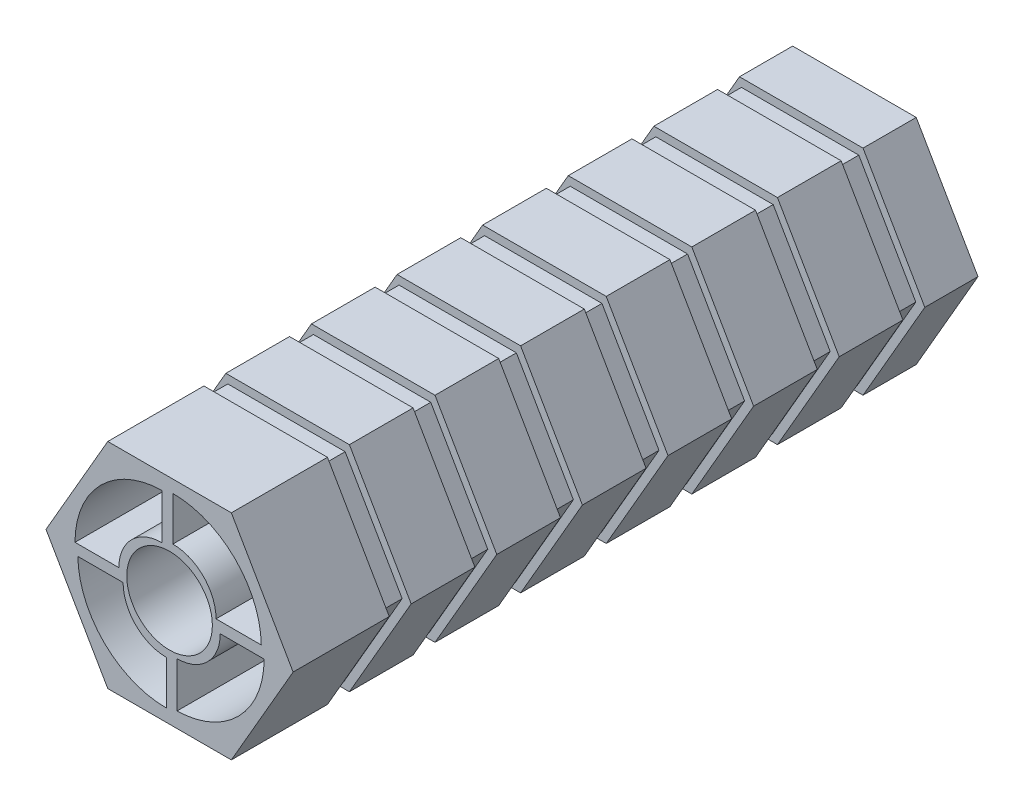
SolidWorks part; units mm, degrees
ref_plane "Front Plane" through (0, 0, 0) normal (0, 0, 1) x (1, 0, 0)
ref_plane "Top Plane" through (0, 0, 0) normal (0, 1, 0) x (1, 0, 0)
ref_plane "Right Plane" through (0, 0, 0) normal (1, 0, 0) x (0, 0, -1)
sketch "Sketch1" plane through (0, 0, 0) normal (0, 0, 1) x (1, 0, 0)
  line L1 (-14.4338, 0) -> (-7.2169, -12.5)
  line L2 (-7.2169, -12.5) -> (7.2169, -12.5)
  line L3 (7.2169, -12.5) -> (14.4338, 0)
  line L4 (14.4338, 0) -> (7.2169, 12.5)
  line L5 (7.2169, 12.5) -> (-7.2169, 12.5)
  line L6 (-7.2169, 12.5) -> (-14.4338, 0)
  circle A0 centre (0, 0) radius 5
  circle A1 centre (0, 0) radius 12.5 construction
  dimension "D1" = 10
  dimension "D2" = 25
extrude "Boss-Extrude1" add sketch "Sketch1" along normal blind 40
sketch "Sketch2" plane through (0, 0, 40) normal (0, 0, 1) x (1, 0, 0)
  line L0 (-0.8762, 10.7144) -> (-0.8762, 5.4289)
  line L1 (-5.9214, 0.3836) -> (-11.0468, 0.3836)
  line L2 (7.2169, 12.5) -> (-7.2169, 12.5) construction
  line L3 (10.7144, 0.8762) -> (5.4289, 0.8762)
  line L4 (0.3836, 5.9214) -> (0.3836, 11.0468)
  line L5 (0.8762, -10.7144) -> (0.8762, -5.4289)
  line L6 (5.9214, -0.3836) -> (11.0468, -0.3836)
  line L7 (-10.7144, -0.8762) -> (-5.4289, -0.8762)
  line L8 (-0.3836, -5.9214) -> (-0.3836, -11.0468)
  arc A0 (-0.8762, 5.4289) -> (-5.9214, 0.3836) centre (-0.8762, 0.3836) ccw
  arc A1 (-11.0468, 0.3836) -> (-0.8762, 10.7144) centre (-0.7147, 0.3836) cw
  arc A2 (0.3836, 11.0468) -> (10.7144, 0.8762) centre (0.3836, 0.7147) cw
  arc A3 (5.4289, 0.8762) -> (0.3836, 5.9214) centre (0.3836, 0.8762) ccw
  arc A4 (11.0468, -0.3836) -> (0.8762, -10.7144) centre (0.7147, -0.3836) cw
  arc A5 (0.8762, -5.4289) -> (5.9214, -0.3836) centre (0.8762, -0.3836) ccw
  arc A6 (-0.3836, -11.0468) -> (-10.7144, -0.8762) centre (-0.3836, -0.7147) cw
  arc A7 (-5.4289, -0.8762) -> (-0.3836, -5.9214) centre (-0.3836, -0.8762) ccw
  point P30 (0, 0)
  dimension "D1" = 10.3321
  dimension "D4" = 1.7856
  dimension "D2" = 5.2855
  dimension "D3" = 5.1254
  dimension "D5" = 3.387
  dimension "D6" = 4
extrude "Cut-Extrude1" cut sketch "Sketch2" against normal through all
sketch "Sketch6" plane through (0, 0, 0) normal (0, 0, -1) x (-1, 0, 0)
  line L0 (-5.4289, 0.8762) -> (-10.7144, 0.8762) construction
  line L1 (-0.3836, 11.0468) -> (-0.3836, 5.9214) construction
  line L2 (-0.8762, -5.4289) -> (-0.8762, -10.7144) construction
  line L3 (0.3836, -11.0468) -> (0.3836, -5.9214) construction
  line L4 (5.4289, -0.8762) -> (10.7144, -0.8762) construction
  line L5 (11.0468, 0.3836) -> (5.9214, 0.3836) construction
  line L6 (14.4338, 0) -> (7.2169, 12.5)
  line L7 (7.2169, 12.5) -> (-7.2169, 12.5)
  line L8 (-7.2169, 12.5) -> (-14.4338, 0)
  line L9 (-14.4338, 0) -> (-7.2169, -12.5)
  line L10 (-7.2169, -12.5) -> (7.2169, -12.5)
  line L11 (7.2169, -12.5) -> (14.4338, 0)
  line L12 (14.4338, 0) -> (7.2169, 12.5)
  line L13 (7.2169, 12.5) -> (-7.2169, 12.5)
  line L14 (-7.2169, 12.5) -> (-14.4338, 0)
  line L15 (-14.4338, 0) -> (-7.2169, -12.5)
  line L16 (-7.2169, -12.5) -> (7.2169, -12.5)
  line L17 (7.2169, -12.5) -> (14.4338, 0)
  line L18 (0.8762, 5.4289) -> (0.8762, 10.7144) construction
  line L19 (-0.8762, -5.4289) -> (-0.8762, -10.7144)
  line L20 (0.3836, -11.0468) -> (0.3836, -5.9214)
  line L21 (5.4289, -0.8762) -> (10.7144, -0.8762)
  line L22 (11.0468, 0.3836) -> (5.9214, 0.3836)
  line L23 (0.8762, 5.4289) -> (0.8762, 10.7144)
  line L24 (-0.3836, 11.0468) -> (-0.3836, 5.9214)
  line L25 (-5.4289, 0.8762) -> (-10.7144, 0.8762)
  arc A0 (-0.3836, 5.9214) -> (-5.4289, 0.8762) centre (-0.3836, 0.8762) ccw construction
  arc A1 (-0.3836, 5.9214) -> (-5.4289, 0.8762) centre (-0.3836, 0.8762) ccw
  arc A2 (-0.3836, 11.0468) -> (-10.7144, 0.8762) centre (-0.3836, 0.7147) ccw construction
  circle A3 centre (0, 0) radius 5 construction
  arc A4 (0.3836, -11.0468) -> (10.7144, -0.8762) centre (0.3836, -0.7147) ccw construction
  arc A5 (-11.0468, -0.3836) -> (-0.8762, -10.7144) centre (-0.7147, -0.3836) ccw construction
  arc A6 (0.3836, -5.9214) -> (5.4289, -0.8762) centre (0.3836, -0.8762) ccw construction
  arc A7 (5.9214, 0.3836) -> (0.8762, 5.4289) centre (0.8762, 0.3836) ccw construction
  arc A8 (11.0468, 0.3836) -> (0.8762, 10.7144) centre (0.7147, 0.3836) ccw construction
  circle A9 centre (0, 0) radius 5
  arc A10 (0.3836, -11.0468) -> (10.7144, -0.8762) centre (0.3836, -0.7147) ccw
  arc A11 (-11.0468, -0.3836) -> (-0.8762, -10.7144) centre (-0.7147, -0.3836) ccw
  arc A12 (0.3836, -5.9214) -> (5.4289, -0.8762) centre (0.3836, -0.8762) ccw
  arc A13 (5.9214, 0.3836) -> (0.8762, 5.4289) centre (0.8762, 0.3836) ccw
  arc A14 (11.0468, 0.3836) -> (0.8762, 10.7144) centre (0.7147, 0.3836) ccw
  arc A15 (-0.3836, 11.0468) -> (-10.7144, 0.8762) centre (-0.3836, 0.7147) ccw
  line M8 (5.4289, -0.8762) -> (10.7144, -0.8762)
  arc M9 (10.7144, -0.8762) -> (0.3836, -11.0468) centre (0.3836, -0.7147) cw
  line M10 (0.3836, -11.0468) -> (0.3836, -5.9214)
  arc M11 (0.3836, -5.9214) -> (5.4289, -0.8762) centre (0.3836, -0.8762) ccw
  line M12 (-0.8762, -5.4289) -> (-0.8762, -10.7144)
  arc M13 (-0.8762, -10.7144) -> (-11.0468, -0.3836) centre (-0.7147, -0.3836) cw
  line M14 (-11.0468, -0.3836) -> (-5.9214, -0.3836)
  arc M15 (-5.9214, -0.3836) -> (-0.8762, -5.4289) centre (-0.8762, -0.3836) ccw
  line M16 (-5.4289, 0.8762) -> (-10.7144, 0.8762)
  arc M17 (-10.7144, 0.8762) -> (-0.3836, 11.0468) centre (-0.3836, 0.7147) cw
  line M18 (-0.3836, 11.0468) -> (-0.3836, 5.9214)
  arc M19 (-0.3836, 5.9214) -> (-5.4289, 0.8762) centre (-0.3836, 0.8762) ccw
  line M20 (0.8762, 5.4289) -> (0.8762, 10.7144)
  arc M21 (0.8762, 10.7144) -> (11.0468, 0.3836) centre (0.7147, 0.3836) cw
  line M22 (11.0468, 0.3836) -> (5.9214, 0.3836)
  arc M23 (5.9214, 0.3836) -> (0.8762, 5.4289) centre (0.8762, 0.3836) ccw
  line M24 (14.4338, 0) -> (7.2169, 12.5)
  line M25 (7.2169, 12.5) -> (-7.2169, 12.5)
  line M26 (-7.2169, 12.5) -> (-14.4338, 0)
  line M27 (-14.4338, 0) -> (-7.2169, -12.5)
  line M28 (-7.2169, -12.5) -> (7.2169, -12.5)
  line M29 (7.2169, -12.5) -> (14.4338, 0)
  circle M30 centre (0, 0) radius 5
  dimension "D1" = 0
extrude "Boss-Extrude2" add sketch "Sketch6" along normal blind 40 contours M29 M24 M25 M26 M27 M28 M30 M23 M20 M21 M22 M19 M16 M17 M18 M15 M12 M13 M14 M11 M8 M9 M10
sketch "Sketch7" plane through (0, -12.5, 0) normal (0, -1, 0) x (1, 0, 0)
  line L0 (-8.4898, -31.2288) -> (-5.5034, -31.2288)
  line L1 (-5.5034, -31.2288) -> (-5.5034, -33.7886)
  line L2 (-5.5034, -33.7886) -> (-8.4898, -33.7886)
  line L3 (-8.4898, -33.7886) -> (-8.4898, -31.2288)
  line L4 (0, 0) -> (0, -49.4423) construction
extrude "Cut-Extrude2" cut sketch "Sketch7" along direction (-0.5, 0.866, 0) on the side against the normal blind 24
sketch "Sketch9" plane through (-10.8253, -6.25, 0) normal (-0.866, -0.5, 0) x (0, 0, 1)
  line L0 (-33.7886, 6.4328) -> (-31.2288, 6.4328)
  line L1 (-33.7886, -7.2169) -> (-33.7886, 7.2169) construction
  line L2 (-31.2288, 8.0736) -> (-31.2288, -0.0895) construction
  line L3 (-31.2288, 6.4328) -> (-31.2288, 8.0736)
  line L4 (-31.2288, 8.0736) -> (-33.7886, 8.0736)
  line L5 (-33.7886, 8.0736) -> (-33.7886, 6.4328)
  line L6 (-23.7886, 8.0736) -> (-23.7886, 6.4328)
  line L7 (-21.2288, 8.0736) -> (-23.7886, 8.0736)
  line L8 (-13.7886, 8.0736) -> (-13.7886, 6.4328)
  line L9 (-11.2288, 8.0736) -> (-13.7886, 8.0736)
  line L10 (-3.7886, 8.0736) -> (-3.7886, 6.4328)
  line L11 (-1.2288, 8.0736) -> (-3.7886, 8.0736)
  line L12 (6.2114, 8.0736) -> (6.2114, 6.4328)
  line L13 (8.7712, 8.0736) -> (6.2114, 8.0736)
  line L14 (16.2114, 8.0736) -> (16.2114, 6.4328)
  line L15 (18.7712, 8.0736) -> (16.2114, 8.0736)
  line L16 (26.2114, 8.0736) -> (26.2114, 6.4328)
  line L17 (28.7712, 8.0736) -> (26.2114, 8.0736)
  line L18 (-23.7886, 6.4328) -> (-21.2288, 6.4328)
  line L19 (-21.2288, 6.4328) -> (-21.2288, 8.0736)
  line L20 (-13.7886, 6.4328) -> (-11.2288, 6.4328)
  line L21 (-11.2288, 6.4328) -> (-11.2288, 8.0736)
  line L22 (-3.7886, 6.4328) -> (-1.2288, 6.4328)
  line L23 (-1.2288, 6.4328) -> (-1.2288, 8.0736)
  line L24 (6.2114, 6.4328) -> (8.7712, 6.4328)
  line L25 (8.7712, 6.4328) -> (8.7712, 8.0736)
  line L26 (16.2114, 6.4328) -> (18.7712, 6.4328)
  line L27 (18.7712, 6.4328) -> (18.7712, 8.0736)
  line L28 (26.2114, 6.4328) -> (28.7712, 6.4328)
  line L29 (28.7712, 6.4328) -> (28.7712, 8.0736)
  dimension "D1" = 7
extrude "Cut-Extrude3" cut sketch "Sketch9" along direction (0.5, 0.866, 0) on the side against the normal blind 24
sketch "Sketch10" plane through (0, -12.5, 0) normal (0, -1, 0) x (1, 0, 0)
  line L1 (-5.5034, -33.7886) -> (-5.5034, -31.2288)
  line L2 (-5.5034, -31.2288) -> (-8.6605, -31.2288)
  line L3 (-14.4338, -31.2288) -> (-7.2169, -31.2288) construction
  line L4 (-8.6605, -31.2288) -> (-8.6605, -33.7886)
  line L5 (-7.2169, -33.7886) -> (-14.4338, -33.7886) construction
  line L6 (-8.6605, -33.7886) -> (-5.5034, -33.7886)
  line L7 (-8.6605, -21.2288) -> (-8.6605, -23.7886)
  line L8 (-8.6605, -23.7886) -> (-5.5034, -23.7886)
  line L9 (-8.6605, -11.2288) -> (-8.6605, -13.7886)
  line L10 (-8.6605, -13.7886) -> (-5.5034, -13.7886)
  line L11 (-8.6605, -1.2288) -> (-8.6605, -3.7886)
  line L12 (-8.6605, -3.7886) -> (-5.5034, -3.7886)
  line L13 (-8.6605, 8.7712) -> (-8.6605, 6.2114)
  line L14 (-8.6605, 6.2114) -> (-5.5034, 6.2114)
  line L15 (-8.6605, 18.7712) -> (-8.6605, 16.2114)
  line L16 (-8.6605, 16.2114) -> (-5.5034, 16.2114)
  line L17 (-8.6605, 28.7712) -> (-8.6605, 26.2114)
  line L18 (-8.6605, 26.2114) -> (-5.5034, 26.2114)
  line L19 (-5.5034, -23.7886) -> (-5.5034, -21.2288)
  line L20 (-5.5034, -21.2288) -> (-8.6605, -21.2288)
  line L21 (-5.5034, -13.7886) -> (-5.5034, -11.2288)
  line L22 (-5.5034, -11.2288) -> (-8.6605, -11.2288)
  line L23 (-5.5034, -3.7886) -> (-5.5034, -1.2288)
  line L24 (-5.5034, -1.2288) -> (-8.6605, -1.2288)
  line L25 (-5.5034, 6.2114) -> (-5.5034, 8.7712)
  line L26 (-5.5034, 8.7712) -> (-8.6605, 8.7712)
  line L27 (-5.5034, 16.2114) -> (-5.5034, 18.7712)
  line L28 (-5.5034, 18.7712) -> (-8.6605, 18.7712)
  line L29 (-5.5034, 26.2114) -> (-5.5034, 28.7712)
  line L30 (-5.5034, 28.7712) -> (-8.6605, 28.7712)
  dimension "D1" = 7
extrude "Cut-Extrude4" cut sketch "Sketch10" along direction (-0.5, 0.866, 0) on the side against the normal blind 24
sketch "Sketch12" plane through (-10.8253, 6.25, 0) normal (-0.866, 0.5, 0) x (0, 0, 1)
  line L1 (-31.2288, 7.2169) -> (-31.2288, 9.2002)
  line L2 (-31.2288, 9.2002) -> (-33.7886, 9.2002)
  line L3 (-33.7886, 9.2002) -> (-33.7886, 7.2169)
  line L4 (-33.7886, 7.2169) -> (-33.7886, 6.1097)
  line L5 (-33.7886, -7.2169) -> (-33.7886, 7.2169) construction
  line L6 (-33.7886, 6.1097) -> (-31.2288, 6.1097)
  line L7 (-31.2288, 7.2169) -> (-31.2288, -7.2169) construction
  line L8 (-31.2288, 6.1097) -> (-31.2288, 7.2169)
  line L9 (-23.7886, 9.2002) -> (-23.7886, 7.2169)
  line L10 (-23.7886, 7.2169) -> (-23.7886, 6.1097)
  line L11 (-21.2288, 6.1097) -> (-21.2288, 7.2169)
  line L12 (-21.2288, 7.2169) -> (-21.2288, 9.2002)
  line L13 (-23.7886, 6.1097) -> (-21.2288, 6.1097)
  line L14 (-13.7886, 9.2002) -> (-13.7886, 7.2169)
  line L15 (-13.7886, 7.2169) -> (-13.7886, 6.1097)
  line L16 (-11.2288, 6.1097) -> (-11.2288, 7.2169)
  line L17 (-11.2288, 7.2169) -> (-11.2288, 9.2002)
  line L18 (-13.7886, 6.1097) -> (-11.2288, 6.1097)
  line L19 (-3.7886, 9.2002) -> (-3.7886, 7.2169)
  line L20 (-3.7886, 7.2169) -> (-3.7886, 6.1097)
  line L21 (-1.2288, 6.1097) -> (-1.2288, 7.2169)
  line L22 (-1.2288, 7.2169) -> (-1.2288, 9.2002)
  line L23 (-3.7886, 6.1097) -> (-1.2288, 6.1097)
  line L24 (6.2114, 9.2002) -> (6.2114, 7.2169)
  line L25 (6.2114, 7.2169) -> (6.2114, 6.1097)
  line L26 (8.7712, 6.1097) -> (8.7712, 7.2169)
  line L27 (8.7712, 7.2169) -> (8.7712, 9.2002)
  line L28 (6.2114, 6.1097) -> (8.7712, 6.1097)
  line L29 (16.2114, 9.2002) -> (16.2114, 7.2169)
  line L30 (16.2114, 7.2169) -> (16.2114, 6.1097)
  line L31 (18.7712, 6.1097) -> (18.7712, 7.2169)
  line L32 (18.7712, 7.2169) -> (18.7712, 9.2002)
  line L33 (16.2114, 6.1097) -> (18.7712, 6.1097)
  line L34 (26.2114, 9.2002) -> (26.2114, 7.2169)
  line L35 (26.2114, 7.2169) -> (26.2114, 6.1097)
  line L36 (28.7712, 6.1097) -> (28.7712, 7.2169)
  line L37 (28.7712, 7.2169) -> (28.7712, 9.2002)
  line L38 (26.2114, 6.1097) -> (28.7712, 6.1097)
  line L39 (-23.7886, 9.2002) -> (-21.2288, 9.2002)
  line L40 (-13.7886, 9.2002) -> (-11.2288, 9.2002)
  line L41 (-3.9144, 9.2002) -> (-1.2288, 9.2002)
  line L42 (6.2114, 9.2002) -> (8.7712, 9.2002)
  line L43 (16.2114, 9.2002) -> (18.7712, 9.2002)
  line L44 (26.2114, 9.2002) -> (28.7712, 9.2002)
  dimension "D1" = 7
extrude "Cut-Extrude5" cut sketch "Sketch12" along direction (1, 0, 0) on the side against the normal blind 24 contours L39 L9 L10 L13 L11 L12 | L40 L14 L15 L18 L16 L17 | L41 L19 L20 L23 L21 L22 | L43 L29 L30 L33 L31 L32 | L44 L34 L35 L38 L36 L37 | L1 L2 L3 L4 L6 L8 | L27 L42 L24 L25 L28 L26
sketch "Sketch15" plane through (0, 12.5, 0) normal (0, 1, 0) x (1, 0, 0)
  line L0 (6.1669, 33.7886) -> (6.1669, 31.2288)
  line L1 (-7.2169, 33.7886) -> (7.2169, 33.7886) construction
  line L2 (7.2169, 31.2288) -> (-7.2169, 31.2288) construction
  line L3 (6.1669, 31.2288) -> (8.3474, 31.2288)
  line L4 (8.3474, 31.2288) -> (8.3474, 33.7886)
  line L5 (8.3474, 33.7886) -> (6.1669, 33.7886)
  line L6 (8.3474, 23.7886) -> (6.1669, 23.7886)
  line L7 (6.1669, 23.7886) -> (6.1669, 21.2288)
  line L8 (6.1669, 21.2288) -> (8.3474, 21.2288)
  line L9 (8.3474, 21.2288) -> (8.3474, 23.7886)
  line L10 (8.3474, 13.7886) -> (6.1669, 13.7886)
  line L11 (6.1669, 13.7886) -> (6.1669, 11.2288)
  line L12 (6.1669, 11.2288) -> (8.3474, 11.2288)
  line L13 (8.3474, 11.2288) -> (8.3474, 13.7886)
  line L14 (8.3474, 3.7886) -> (6.1669, 3.7886)
  line L15 (6.1669, 3.7886) -> (6.1669, 1.2288)
  line L16 (6.1669, 1.2288) -> (8.3474, 1.2288)
  line L17 (8.3474, 1.2288) -> (8.3474, 3.7886)
  line L18 (8.3474, -6.2114) -> (6.1669, -6.2114)
  line L19 (6.1669, -6.2114) -> (6.1669, -8.7712)
  line L20 (6.1669, -8.7712) -> (8.3474, -8.7712)
  line L21 (8.3474, -8.7712) -> (8.3474, -6.2114)
  line L22 (8.3474, -16.2114) -> (6.1669, -16.2114)
  line L23 (6.1669, -16.2114) -> (6.1669, -18.7712)
  line L24 (6.1669, -18.7712) -> (8.3474, -18.7712)
  line L25 (8.3474, -18.7712) -> (8.3474, -16.2114)
  line L26 (8.3474, -26.2114) -> (6.1669, -26.2114)
  line L27 (6.1669, -26.2114) -> (6.1669, -28.7712)
  line L28 (6.1669, -28.7712) -> (8.3474, -28.7712)
  line L29 (8.3474, -28.7712) -> (8.3474, -26.2114)
  dimension "D1" = 7
extrude "Cut-Extrude6" cut sketch "Sketch15" along direction (0.5, -0.866, 0) on the side against the normal blind 24
sketch "Sketch16" plane through (10.8253, 6.25, 0) normal (0.866, 0.5, 0) x (0, 0, -1)
  line L0 (33.7886, -6.1626) -> (31.2288, -6.1626)
  line L1 (33.7886, 7.2169) -> (33.7886, -7.2169) construction
  line L2 (31.2288, -7.2169) -> (31.2288, 7.2169) construction
  line L3 (31.2288, -6.1626) -> (31.2288, -9.149)
  line L4 (31.2288, -9.149) -> (33.7886, -9.149)
  line L5 (33.7886, -9.149) -> (33.7886, -6.1626)
  line L6 (23.7886, -9.149) -> (23.7886, -6.1626)
  line L7 (23.7886, -6.1626) -> (21.2288, -6.1626)
  line L8 (21.2288, -6.1626) -> (21.2288, -9.149)
  line L9 (21.2288, -9.149) -> (23.7886, -9.149)
  line L10 (13.7886, -9.149) -> (13.7886, -6.1626)
  line L11 (13.7886, -6.1626) -> (11.2288, -6.1626)
  line L12 (11.2288, -6.1626) -> (11.2288, -9.149)
  line L13 (11.2288, -9.149) -> (13.7886, -9.149)
  line L14 (3.7886, -9.149) -> (3.7886, -6.1626)
  line L15 (3.7886, -6.1626) -> (1.2288, -6.1626)
  line L16 (1.2288, -6.1626) -> (1.2288, -9.149)
  line L17 (1.2288, -9.149) -> (3.7886, -9.149)
  line L18 (-6.2114, -9.149) -> (-6.2114, -6.1626)
  line L19 (-6.2114, -6.1626) -> (-8.7712, -6.1626)
  line L20 (-8.7712, -6.1626) -> (-8.7712, -9.149)
  line L21 (-8.7712, -9.149) -> (-6.2114, -9.149)
  line L22 (-16.2114, -9.149) -> (-16.2114, -6.1626)
  line L23 (-16.2114, -6.1626) -> (-18.7712, -6.1626)
  line L24 (-18.7712, -6.1626) -> (-18.7712, -9.149)
  line L25 (-18.7712, -9.149) -> (-16.2114, -9.149)
  line L26 (-26.2114, -9.149) -> (-26.2114, -6.1626)
  line L27 (-26.2114, -6.1626) -> (-28.7712, -6.1626)
  line L28 (-28.7712, -6.1626) -> (-28.7712, -9.149)
  line L29 (-28.7712, -9.149) -> (-26.2114, -9.149)
  dimension "D1" = 7
extrude "Cut-Extrude7" cut sketch "Sketch16" along direction (-0.5, -0.866, 0) on the side against the normal blind 24
sketch "Sketch17" plane through (10.8253, -6.25, 0) normal (0.866, -0.5, 0) x (0, 0, -1)
  line L0 (-26.2114, -6.4407) -> (-28.7712, -6.4407)
  line L1 (-26.2114, -7.744) -> (-26.2114, 6.6941) construction
  line L2 (-28.7712, -7.2169) -> (-28.7712, 7.2169) construction
  line L3 (-28.7712, -6.4407) -> (-28.7712, -9.1942)
  line L4 (-28.7712, -9.1942) -> (-26.2114, -9.1942)
  line L5 (-26.2114, -9.1942) -> (-26.2114, -6.4407)
  line L6 (-16.2114, -9.1942) -> (-16.2114, -6.4407)
  line L7 (-16.2114, -6.4407) -> (-18.7712, -6.4407)
  line L8 (-18.7712, -6.4407) -> (-18.7712, -9.1942)
  line L9 (-18.7712, -9.1942) -> (-16.2114, -9.1942)
  line L10 (-6.2114, -9.1942) -> (-6.2114, -6.4407)
  line L11 (-6.2114, -6.4407) -> (-8.7712, -6.4407)
  line L12 (-8.7712, -6.4407) -> (-8.7712, -9.1942)
  line L13 (-8.7712, -9.1942) -> (-6.2114, -9.1942)
  line L14 (3.7886, -9.1942) -> (3.7886, -6.4407)
  line L15 (3.7886, -6.4407) -> (1.2288, -6.4407)
  line L16 (1.2288, -6.4407) -> (1.2288, -9.1942)
  line L17 (1.2288, -9.1942) -> (3.7886, -9.1942)
  line L18 (13.7886, -9.1942) -> (13.7886, -6.4407)
  line L19 (13.7886, -6.4407) -> (11.2288, -6.4407)
  line L20 (11.2288, -6.4407) -> (11.2288, -9.1942)
  line L21 (11.2288, -9.1942) -> (13.7886, -9.1942)
  line L22 (23.7886, -9.1942) -> (23.7886, -6.4407)
  line L23 (23.7886, -6.4407) -> (21.2288, -6.4407)
  line L24 (21.2288, -6.4407) -> (21.2288, -9.1942)
  line L25 (21.2288, -9.1942) -> (23.7886, -9.1942)
  line L26 (33.7886, -9.1942) -> (33.7886, -6.4407)
  line L27 (33.7886, -6.4407) -> (31.2288, -6.4407)
  line L28 (31.2288, -6.4407) -> (31.2288, -9.1942)
  line L29 (31.2288, -9.1942) -> (33.7886, -9.1942)
  dimension "D1" = 7
extrude "Cut-Extrude8" cut sketch "Sketch17" along direction (1, 0, 0) on the side against the normal blind 24
